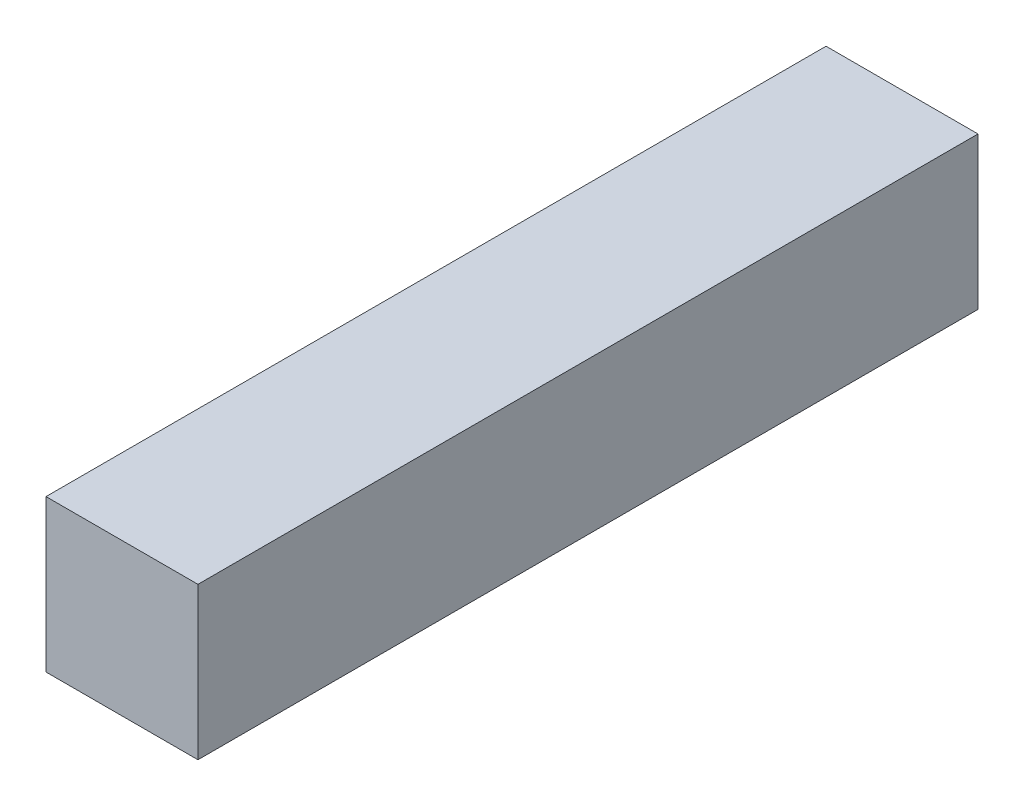
SolidWorks part; units mm, degrees
ref_plane "Спереди" through (0, 0, 0) normal (0, 0, 1) x (1, 0, 0)
ref_plane "Сверху" through (0, 0, 0) normal (0, 1, 0) x (1, 0, 0)
ref_plane "Справа" through (0, 0, 0) normal (1, 0, 0) x (0, 0, -1)
sketch "Эскиз профиля" plane through (0, 0, 0) normal (0, 0, 1) x (1, 0, 0)
  line L1 (-7.5, 7.5) -> (7.5, 7.5)
  line L2 (-7.5, 7.5) -> (-7.5, -7.5)
  line L3 (-7.5, -7.5) -> (7.5, -7.5)
  line L4 (7.5, 7.5) -> (7.5, -7.5)
  line L5 (-7.5, 7.5) -> (7.5, -7.5) construction
  line L6 (-7.5, -7.5) -> (7.5, 7.5) construction
  point P0 (0, 0)
  dimension "D1" = 15
  dimension "D2" = 15
extrude "Бобышка-Вытянуть1" add sketch "Эскиз профиля" along normal blind 77
